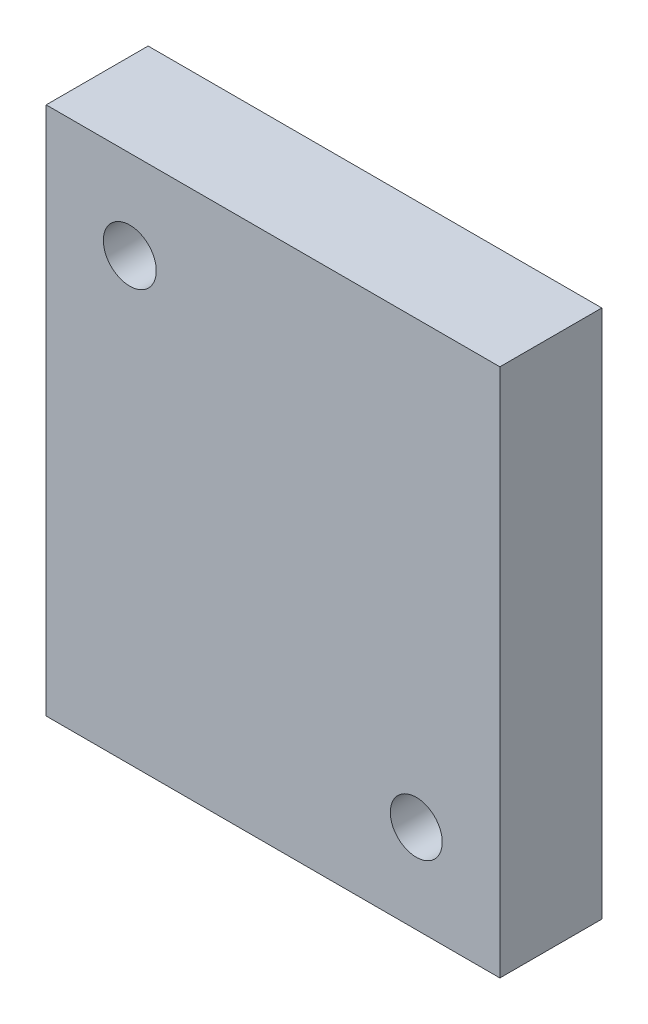
SolidWorks part; units mm, degrees
ref_plane "Front Plane" through (0, 0, 0) normal (0, 0, 1) x (1, 0, 0)
ref_plane "Top Plane" through (0, 0, 0) normal (0, 1, 0) x (1, 0, 0)
ref_plane "Right Plane" through (0, 0, 0) normal (1, 0, 0) x (0, 0, -1)
sketch "Sketch1" plane through (0, 0, 0) normal (0, 0, 1) x (1, 0, 0)
  line L1 (-30, 35) -> (30, 35)
  line L2 (-30, 35) -> (-30, -35)
  line L3 (-30, -35) -> (30, -35)
  line L4 (30, 35) -> (30, -35)
  line L5 (-30, 35) -> (30, -35) construction
  line L6 (-30, -35) -> (30, 35) construction
  point P0 (0, 0)
  dimension "D1" = 70
  dimension "D2" = 60
extrude "Boss-Extrude1" add sketch "Sketch1" along normal blind 13.48
sketch "Sketch2" plane through (0, 0, 0) normal (0, 0, -1) x (-1, 0, 0)
  circle A0 centre (-18.9425, -23.2633) radius 3.4349
  circle A1 centre (18.9425, 23.2633) radius 3.5
extrude "Cut-Extrude1" cut sketch "Sketch2" against normal blind 29
